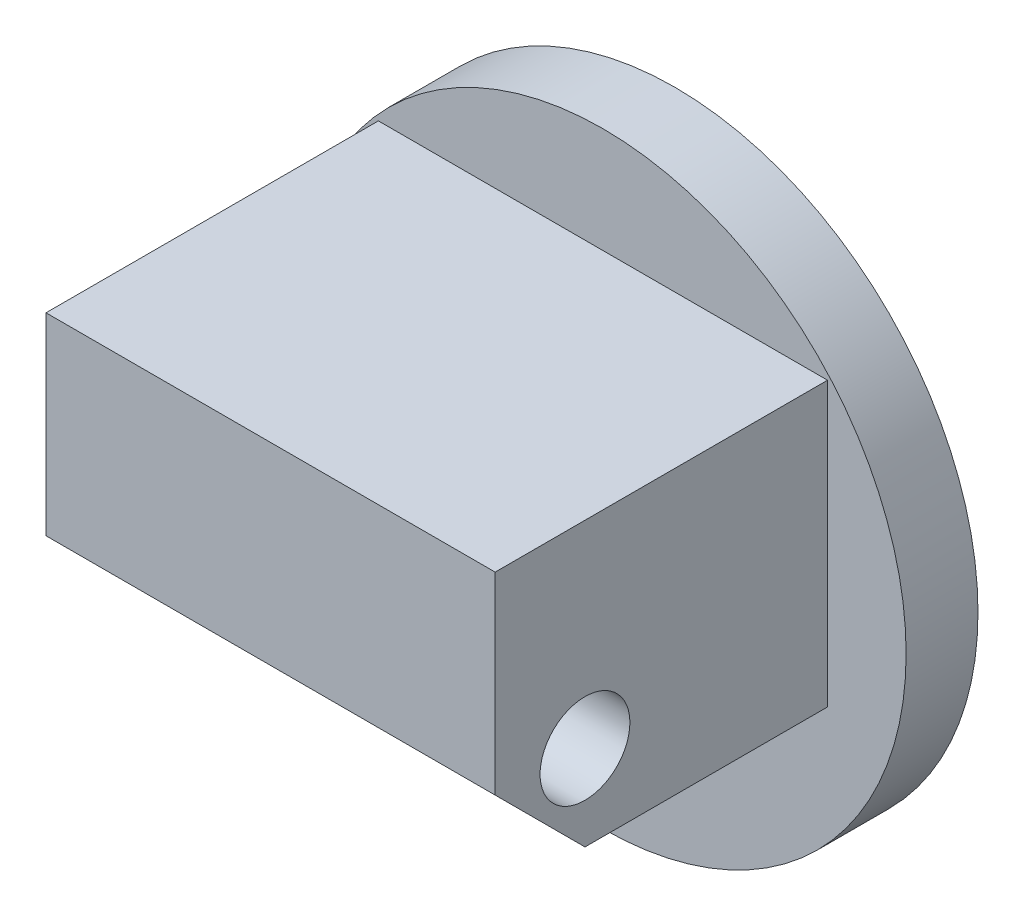
SolidWorks part; units mm, degrees
ref_plane "Front Plane" through (0, 0, 0) normal (0, 0, 1) x (1, 0, 0)
ref_plane "Top Plane" through (0, 0, 0) normal (0, 1, 0) x (1, 0, 0)
ref_plane "Right Plane" through (0, 0, 0) normal (1, 0, 0) x (0, 0, -1)
sketch "Sketch1" plane through (0, 0, 0) normal (0, 0, 1) x (1, 0, 0)
  circle A0 centre (0, 0) radius 6.75
  dimension "D1" = 13.5
extrude "Boss-Extrude1" add sketch "Sketch1" along normal blind 9
sketch "Sketch2" plane through (0, 0, 0) normal (0, 0, -1) x (-1, 0, 0)
  circle A0 centre (0, 0) radius 5
  dimension "D1" = 10
extrude "Boss-Extrude2" add sketch "Sketch2" along normal blind 1
sketch "Sketch3" plane through (0, 0, 0) normal (0, 1, 0) x (1, 0, 0)
  line L0 (0, 0) -> (0, -9) construction
  line L1 (-6.75, -9) -> (6.75, -9) construction
  line L2 (-6.75, 0) -> (-6.75, -9) construction
  line L3 (-6.75, -1.6) -> (-5, -1.6)
  line L4 (-6.75, -1.6) -> (-6.75, -9)
  line L5 (-6.75, -9) -> (-5, -9)
  line L6 (-5, -1.6) -> (-5, -9)
  line L7 (6.75, 0) -> (-6.75, 0) construction
  line L8 (5, -1.6) -> (5, -9)
  line L9 (6.75, -9) -> (5, -9)
  line L10 (6.75, -1.6) -> (6.75, -9)
  line L11 (6.75, -1.6) -> (5, -1.6)
  dimension "D1" = 1.6
  dimension "D2" = 10
extrude "Cut-Extrude1" cut sketch "Sketch3" against normal through all both and the other way through all
sketch "Sketch4" plane through (0, 0, 0) normal (1, 0, 0) x (0, 0, -1)
  line L0 (-9, 4.5346) -> (-9, -4.5346) construction
  line L1 (-9, 4.4) -> (-1.6, 4.4)
  line L2 (-9, 4.4) -> (-9, -1.9)
  line L3 (-9, -1.9) -> (-1.6, -1.9)
  line L4 (-1.6, 4.4) -> (-1.6, -1.9)
  line L5 (-1.6, 4.5346) -> (-1.6, -4.5346) construction
  line L6 (-9, -6.75) -> (0, -6.75) construction
  line L7 (0, 6.75) -> (-9, 6.75) construction
  line L8 (-9, -1.9) -> (-1.6, -1.9)
  line L9 (-9, -1.9) -> (-9, -6.75)
  line L10 (-9, -6.75) -> (-1.6, -6.75)
  line L11 (-1.6, -1.9) -> (-1.6, -6.75)
  line L12 (-9, 4.4) -> (-1.6, 4.4)
  line L13 (-9, 4.4) -> (-9, 6.75)
  line L14 (-9, 6.75) -> (-1.6, 6.75)
  line L15 (-1.6, 4.4) -> (-1.6, 6.75)
  dimension "D1" = 6.3
  dimension "D2" = 4.85
extrude "Cut-Extrude2" cut sketch "Sketch4" against normal through all both and the other way through all contours L11 L3 L9 L10 | L1 L15 L14 L13
sketch "Sketch5" plane through (5, 0, 0) normal (1, 0, 0) x (0, 0, -1)
  circle A0 centre (-7, 0) radius 1
  dimension "D2" = 2
  dimension "D1" = 7
extrude "Cut-Extrude3" cut sketch "Sketch5" against normal through all both
chamfer "Chamfer1" distance 2 1 edges at (0, -1.9, 9)
